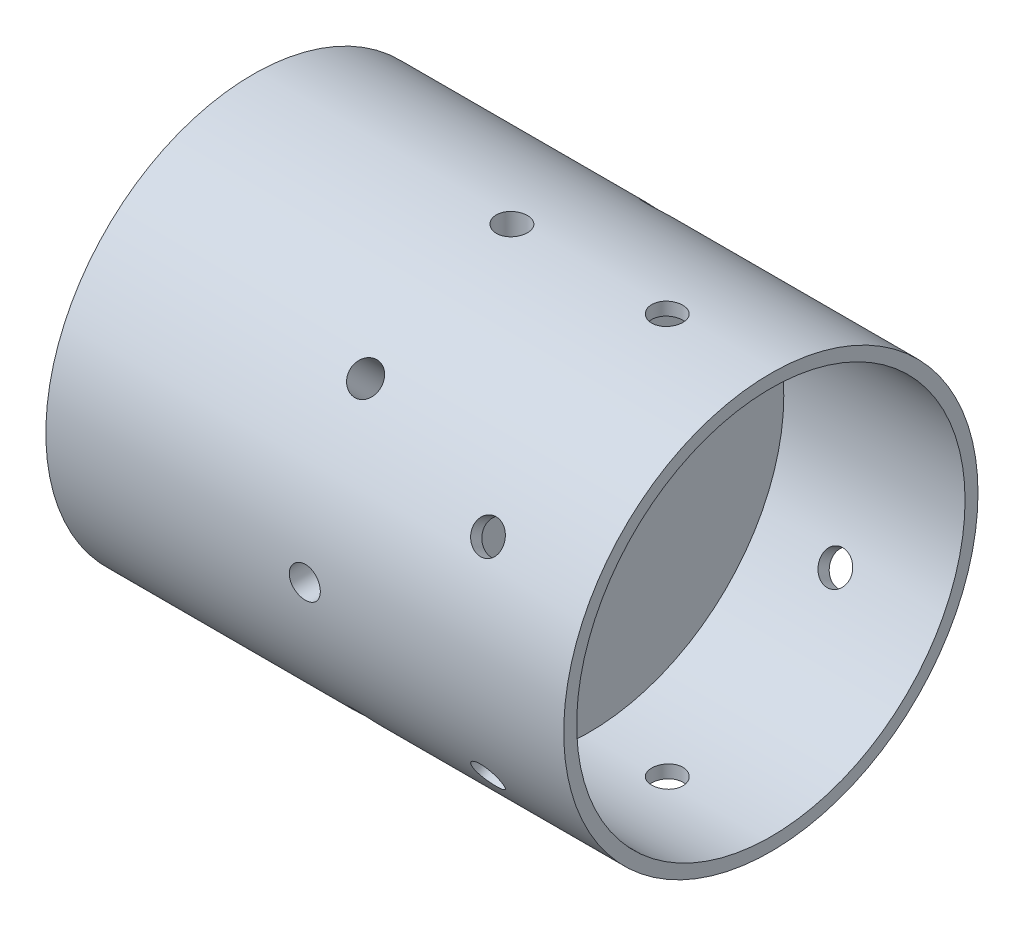
SolidWorks part; units mm, degrees
material "ABS"
ref_plane "Front Plane" through (0, 0, 0) normal (0, 0, 1) x (1, 0, 0)
ref_plane "Top Plane" through (0, 0, 0) normal (0, 1, 0) x (1, 0, 0)
ref_plane "Right Plane" through (0, 0, 0) normal (1, 0, 0) x (0, 0, -1)
sketch "Sketch1" plane through (0, 0, 0) normal (1, 0, 0) x (0, 0, -1)
  circle A0 centre (0, 0) radius 40
  dimension "D1" = 80
extrude "Boss-Extrude1" add sketch "Sketch1" along normal mid plane 100
ref_plane "Bolts" through (0, 40, 0) normal (0, 1, 0) x (1, 0, 0)
sketch "Sketch4" plane through (0, 40, 0) normal (0, 1, 0) x (1, 0, 0)
  line L0 (-50, 0) -> (50, 0) construction
  line L1 (50, -40) -> (50, 40) construction
  circle A0 centre (0, 0) radius 3
  circle A1 centre (30, 0) radius 3
  point P6 (0, 0)
  dimension "D3" = 6
  dimension "D1" = 30
  dimension "D2" = 50
extrude "Cut-Extrude2" cut sketch "Sketch4" against normal blind 15 contours A0
pattern_circular "CirPattern1" count 8 over 360 about axis through (0, 0, 0) along (1, 0, 0) of "Cut-Extrude2"
sketch "Sketch5" plane through (-50, 0, 0) normal (-1, 0, 0) x (0, 0, 1)
  line L0 (0, 0) -> (14.8524, 26.0654) construction
  circle A0 centre (0, 0) radius 30 construction
  circle A1 centre (14.8524, 26.0654) radius 2.5
  circle A2 centre (0, 0) radius 30 construction
  circle A4 centre (-14.8524, -26.0654) radius 2.5 [skipped]
  circle A15 centre (29.9995, 0.1701) radius 2.5
  circle A16 centre (15.1471, -25.8953) radius 2.5
  circle A17 centre (-14.8524, -26.0654) radius 2.5
  circle A18 centre (-29.9995, -0.1701) radius 2.5
  circle A19 centre (-15.1471, 25.8953) radius 2.5
  point P14 (-0.0022, 0.0013)
  point P22 (0, 0)
  point P33 (0, 0)
  dimension "D1" = 60
  dimension "D2" = 5
  dimension "D4" = 2
extrude "Cut-Extrude5" cut sketch "Sketch5" against normal blind 15
sketch "Sketch6" plane through (50, 0, 0) normal (1, 0, 0) x (0, 0, -1)
  circle A0 centre (0, 0) radius 37.5
  circle A1 centre (0, 0) radius 40 construction
  dimension "D1" = 2.5
extrude "Cut-Extrude6" cut sketch "Sketch6" against normal blind 35
ref_plane "Plane1" through (0, 40, 0) normal (0, 1, 0) x (1, 0, 0)
sketch "Sketch7" plane through (0, 40, 0) normal (0, 1, 0) x (1, 0, 0)
  circle A0 centre (30, 0) radius 3 construction
  circle A1 centre (30, 0) radius 3
extrude "Cut-Extrude9" cut sketch "Sketch7" against normal up to surface (2.6202 mm away)
pattern_circular "CirPattern3" count 6 over 360 about axis through (50, 0, 0) along (-1, 0, 0) of "Cut-Extrude9"
